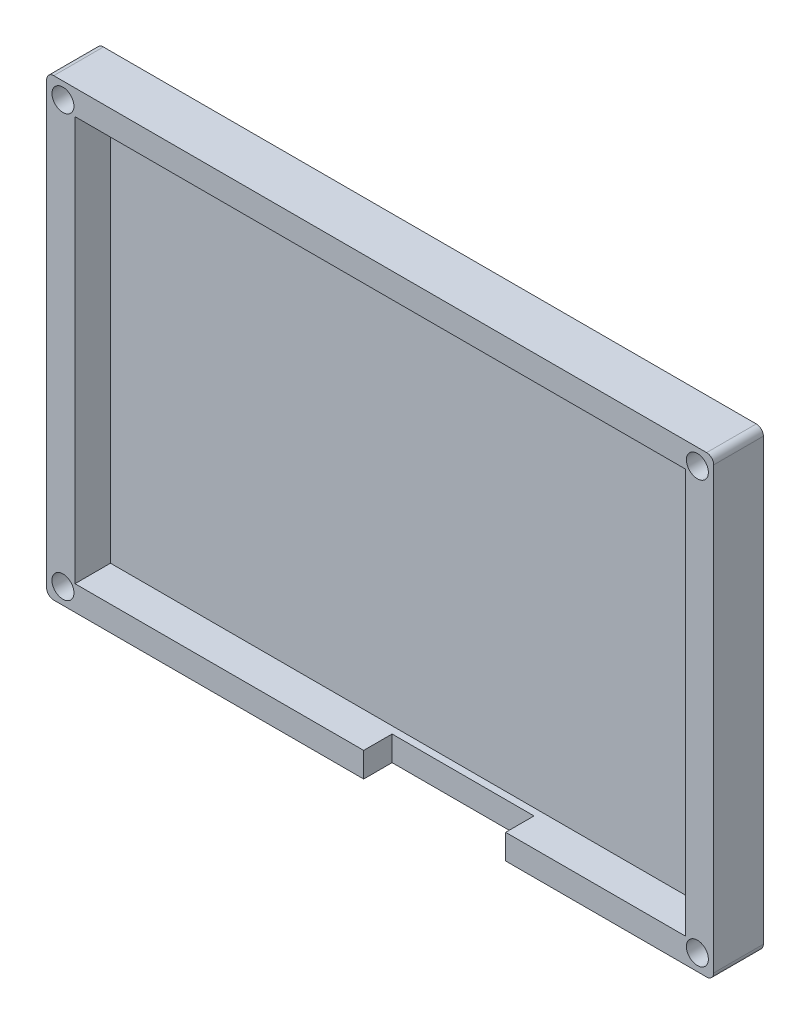
SolidWorks part; units mm, degrees
ref_plane "前视基准面" through (0, 0, 0) normal (0, 0, 1) x (1, 0, 0)
ref_plane "上视基准面" through (0, 0, 0) normal (0, 1, 0) x (1, 0, 0)
ref_plane "右视基准面" through (0, 0, 0) normal (1, 0, 0) x (0, 0, -1)
sketch "草图1" plane through (0, 0, 0) normal (0, 0, 1) x (1, 0, 0)
  line L1 (-47, -32) -> (47, -32)
  line L2 (-47, -32) -> (-47, 32)
  line L3 (-47, 32) -> (47, 32)
  line L4 (47, -32) -> (47, 32)
  line L5 (-47, -32) -> (47, 32) construction
  line L6 (-47, 32) -> (47, -32) construction
  point P0 (0, 0)
  dimension "D1" = 94
  dimension "D2" = 64
extrude "凸台-拉伸1" add sketch "草图1" along normal blind 7
fillet "圆角1" radius 1 4 edges at (47, -32, 3.5) (-47, -32, 3.5) (-47, 32, 3.5) (47, 32, 3.5)
sketch "草图2" plane through (0, 0, 7) normal (0, 0, 1) x (1, 0, 0)
  line L1 (-43, -28.5) -> (43, -28.5)
  line L2 (-43, -28.5) -> (-43, 28.5)
  line L3 (-43, 28.5) -> (43, 28.5)
  line L4 (43, -28.5) -> (43, 28.5)
  line L5 (-43, -28.5) -> (43, 28.5) construction
  line L6 (-43, 28.5) -> (43, -28.5) construction
  point P0 (0, 0)
  dimension "D1" = 86
  dimension "D2" = 57
extrude "切除-拉伸1" cut sketch "草图2" against normal blind 5
sketch "草图3" plane through (0, 0, 7) normal (0, 0, 1) x (1, 0, 0)
  line L0 (46, 32) -> (-46, 32) construction
  line L1 (-47, 31) -> (-47, -31) construction
  line L2 (0, -3.85) -> (0, 3.85) construction
  line L3 (3.85, 0) -> (-3.85, 0) construction
  circle A0 centre (-44.7, 29.7) radius 1.55
  circle A1 centre (44.7, 29.7) radius 1.55
  circle A2 centre (44.7, -29.7) radius 1.55
  circle A3 centre (-44.7, -29.7) radius 1.55
  dimension "D1" = 2.3
  dimension "D2" = 2.3
extrude "切除-拉伸2" cut sketch "草图3" against normal through all
sketch "草图4" plane through (0, -32, 0) normal (0, -1, 0) x (1, 0, 0)
  line L0 (-46, 0) -> (46, 0) construction
  line L1 (-2.32, 8) -> (17.68, 8)
  line L2 (-2.32, 8) -> (-2.32, 3)
  line L3 (-2.32, 3) -> (17.68, 3)
  line L4 (17.68, 8) -> (17.68, 3)
  line L6 (-47, 0) -> (-47, 7) construction
  dimension "D1" = 20
  dimension "D2" = 5
  dimension "D3" = 3
  dimension "D4" = 44.68
extrude "切除-拉伸4" cut sketch "草图4" against normal blind 5
